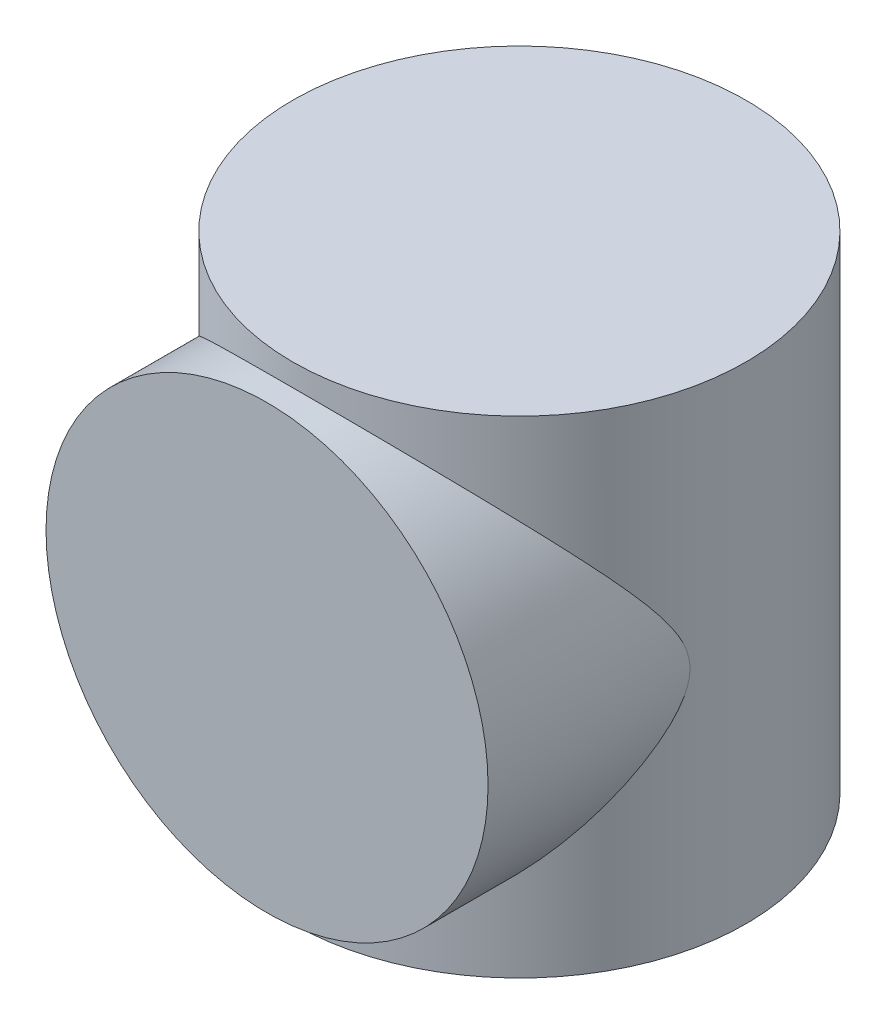
SolidWorks part; units mm, degrees
ref_plane "Front Plane" through (0, 0, 0) normal (0, 0, 1) x (1, 0, 0)
ref_plane "Top Plane" through (0, 0, 0) normal (0, 1, 0) x (1, 0, 0)
ref_plane "Right Plane" through (0, 0, 0) normal (1, 0, 0) x (0, 0, -1)
sketch "Sketch1" plane through (0, 0, 0) normal (0, 1, 0) x (1, 0, 0)
  circle A0 centre (0, 0) radius 53.9
  dimension "D1" = 107.8
extrude "Boss-Extrude1" add sketch "Sketch1" along normal blind 115.7
sketch "Sketch2" plane through (0, 0, 0) normal (0, 0, 1) x (1, 0, 0)
  line L0 (53.9, 115.7) -> (-53.9, 115.7) construction
  circle A0 centre (0, 57.85) radius 52.55
  point P2 (0, 0)
  point P4 (0, 57.2772)
  dimension "D1" = 105.1
  dimension "D2" = 57.85
extrude "Boss-Extrude2" add sketch "Sketch2" along normal blind 60
